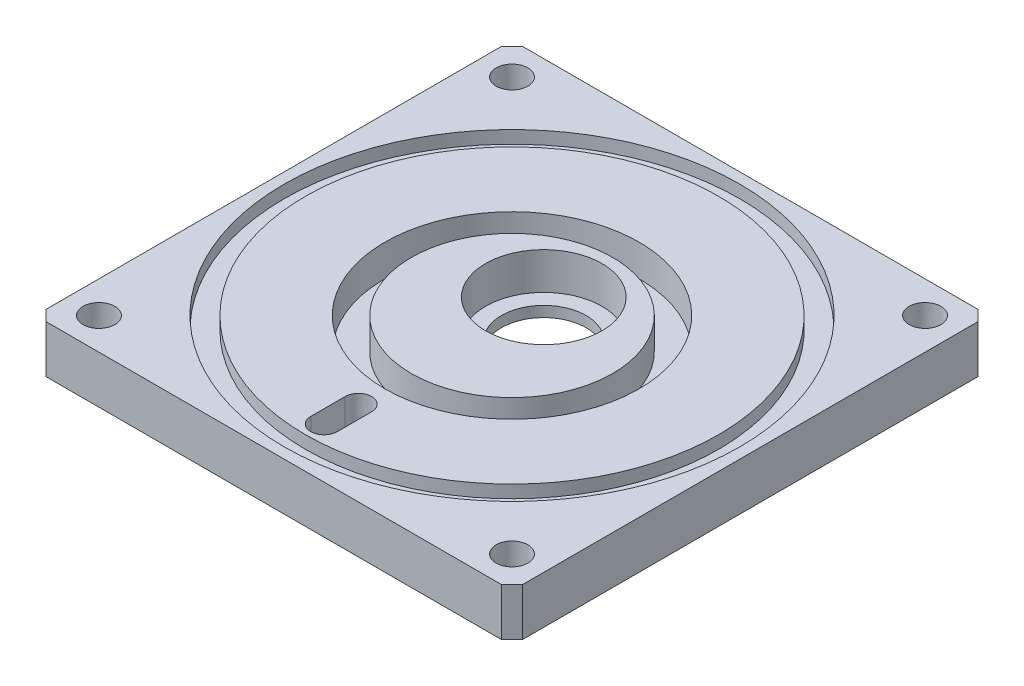
SolidWorks part; units mm, degrees
ref_plane "前视基准面" through (0, 0, 0) normal (0, 0, 1) x (1, 0, 0)
ref_plane "上视基准面" through (0, 0, 0) normal (0, 1, 0) x (1, 0, 0)
ref_plane "右视基准面" through (0, 0, 0) normal (1, 0, 0) x (0, 0, -1)
sketch "草图1" plane through (0, 0, 0) normal (0, 1, 0) x (1, 0, 0)
  line L1 (-22.5, -22.5) -> (22.5, -22.5)
  line L2 (-22.5, -22.5) -> (-22.5, 22.5)
  line L3 (-22.5, 22.5) -> (22.5, 22.5)
  line L4 (22.5, -22.5) -> (22.5, 22.5)
  line L5 (-22.5, -22.5) -> (22.5, 22.5) construction
  line L6 (-22.5, 22.5) -> (22.5, -22.5) construction
  point P0 (0, 0)
  dimension "D1" = 45
  dimension "D2" = 45
extrude "凸台-拉伸1" add sketch "草图1" along normal blind 4.5
sketch "草图2" plane through (0, 4.5, 0) normal (0, 1, 0) x (1, 0, 0)
  line L0 (0, 0) -> (0, 3) construction
  circle A0 centre (0, 3) radius 5.5
  dimension "D2" = 11
  dimension "D1" = 3
extrude "切除-拉伸1" cut sketch "草图2" against normal blind 3.5
sketch "草图3" plane through (0, 1, 0) normal (0, 1, 0) x (1, 0, 0)
  circle A0 centre (0, 3) radius 4
  dimension "D1" = 8
extrude "切除-拉伸2" cut sketch "草图3" against normal through all
sketch "草图4" plane through (0, 4.5, 0) normal (0, 1, 0) x (1, 0, 0)
  circle A0 centre (0, 0) radius 9.5
  circle A1 centre (0, 0) radius 12
  dimension "D1" = 19
  dimension "D2" = 24
extrude "切除-拉伸3" cut sketch "草图4" against normal blind 3
sketch "草图5" plane through (0, 4.5, 0) normal (0, 1, 0) x (1, 0, 0)
  circle A0 centre (0, 0) radius 19.5
  circle A1 centre (0, 0) radius 21.5
  dimension "D1" = 43
  dimension "D2" = 39
extrude "切除-拉伸4" cut sketch "草图5" against normal blind 1.2
sketch "草图6" plane through (0, 4.5, 0) normal (0, 1, 0) x (1, 0, 0)
  line L0 (0, -19) -> (0, -14.5) construction
  line L1 (0, -14.5) -> (0, -17.75) construction
  line L2 (1.25, -14.5) -> (1.25, -17.75)
  line L3 (-1.25, -14.5) -> (-1.25, -17.75)
  circle A0 centre (0, 0) radius 19 construction
  arc A1 (1.25, -14.5) -> (-1.25, -14.5) centre (0, -14.5) ccw
  arc A2 (-1.25, -17.75) -> (1.25, -17.75) centre (0, -17.75) ccw
  point P5 (0, -16.125)
  dimension "D1" = 38
  dimension "D2" = 4.5
  dimension "D3" = 1.25
extrude "切除-拉伸5" cut sketch "草图6" against normal through all
sketch "草图8" plane through (0, 0, 0) normal (0, -1, 0) x (1, 0, 0)
  line L0 (0, 22.5) -> (0, -22.5) construction
  line L1 (-22.5, 22.5) -> (22.5, 22.5) construction
  line L2 (22.5, -22.5) -> (-22.5, -22.5) construction
  line L3 (-22.5, 0) -> (22.5, 0) construction
  line L4 (-22.5, -22.5) -> (-22.5, 22.5) construction
  line L5 (22.5, 22.5) -> (22.5, -22.5) construction
  circle A0 centre (-19.5, 19.5) radius 1.5
  circle A1 centre (19.5, 19.5) radius 1.5
  circle A2 centre (19.5, -19.5) radius 1.5
  circle A3 centre (-19.5, -19.5) radius 1.5
  dimension "D1" = 3
  dimension "D2" = 3
  dimension "D3" = 3
extrude "切除-拉伸6" cut sketch "草图8" against normal through all
chamfer "倒角1" distance 1 angle 45 4 edges at (22.5, 2.25, -22.5) (22.5, 2.25, 22.5) (-22.5, 2.25, 22.5) (-22.5, 2.25, -22.5)
